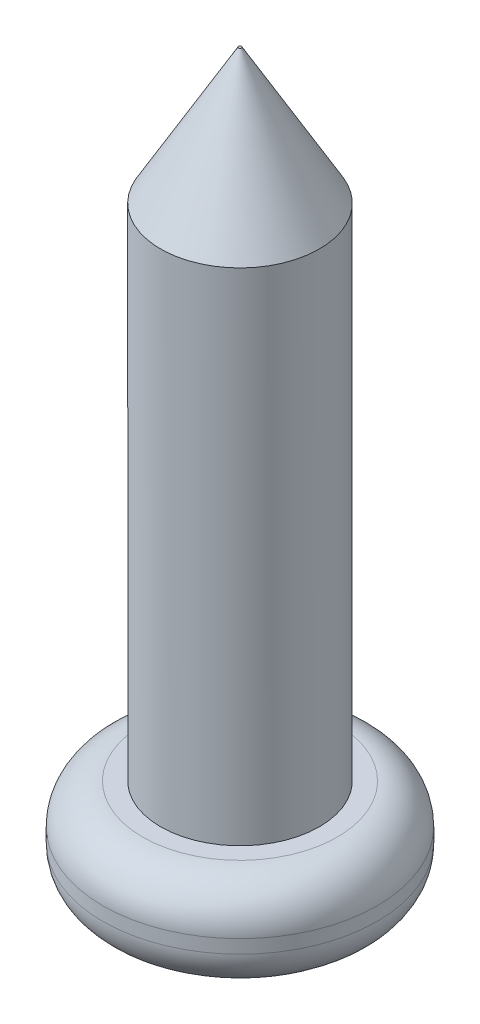
SolidWorks part; units mm, degrees
ref_plane "前视基准面" through (0, 0, 0) normal (0, 0, 1) x (1, 0, 0)
ref_plane "上视基准面" through (0, 0, 0) normal (0, 1, 0) x (1, 0, 0)
ref_plane "右视基准面" through (0, 0, 0) normal (1, 0, 0) x (0, 0, -1)
sketch "草图1" plane through (0, 0, 0) normal (0, 1, 0) x (1, 0, 0)
  circle A0 centre (0, 0) radius 1.725
  dimension "D1" = 3.45
extrude "凸台-拉伸1" add sketch "草图1" along normal blind 1.17
fillet "圆角1" radius 0.5 2 edges at (0, 0, 1.725) (0, 1.17, 1.725)
sketch "草图2" plane through (0, 1.17, 0) normal (0, 1, 0) x (1, 0, 0)
  circle A0 centre (0, 0) radius 1
  dimension "D1" = 2
extrude "凸台-拉伸2" add sketch "草图2" along normal blind 8
chamfer "倒角1" distance 1.7 angle 30 1 edges at (0, 9.17, 1)
